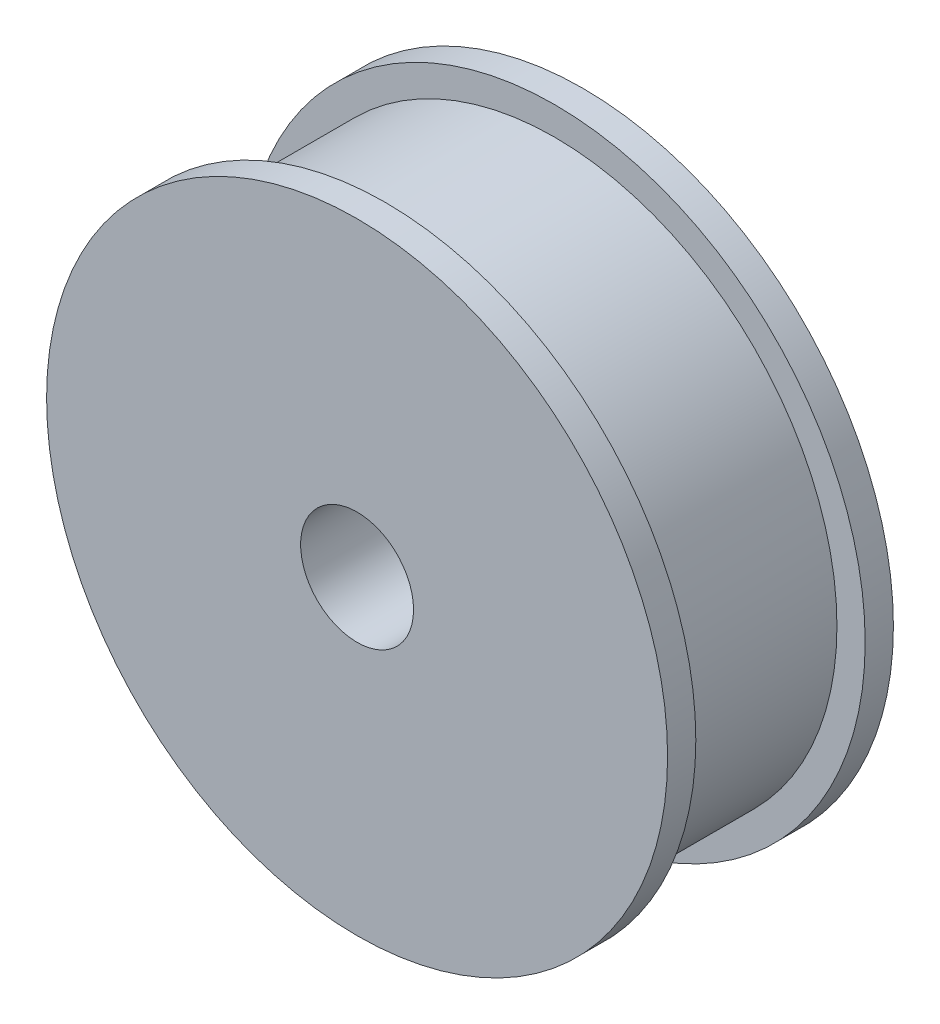
SolidWorks part; units mm, degrees
ref_plane "前视" through (0, 0, 0) normal (0, 0, 1) x (1, 0, 0)
ref_plane "上视" through (0, 0, 0) normal (0, 1, 0) x (1, 0, 0)
ref_plane "右视" through (0, 0, 0) normal (1, 0, 0) x (0, 0, -1)
sketch "草图1" plane through (0, 0, 0) normal (0, 0, 1) x (1, 0, 0)
  circle A0 centre (0, 0) radius 16.5
  dimension "D1" = 33
extrude "凸台-拉伸1" add sketch "草图1" along normal blind 12
ref_plane "基准面1" through (0, 0, 6) normal (0, 0, 1) x (1, 0, 0)
sketch "草图2" plane through (0, 0, 6) normal (0, 0, 1) x (1, 0, 0)
  circle A0 centre (0, 0) radius 15
  circle A1 centre (0, 0) radius 19.5
  dimension "D1" = 30
  dimension "D2" = 39
extrude "切除-拉伸1" cut sketch "草图2" against normal blind 4.5 and the other way blind 4.5
sketch "草图3" plane through (0, 0, 12) normal (0, 0, 1) x (1, 0, 0)
  circle A0 centre (0, 0) radius 3
  dimension "D1" = 6
extrude "切除-拉伸2" cut sketch "草图3" against normal through all
